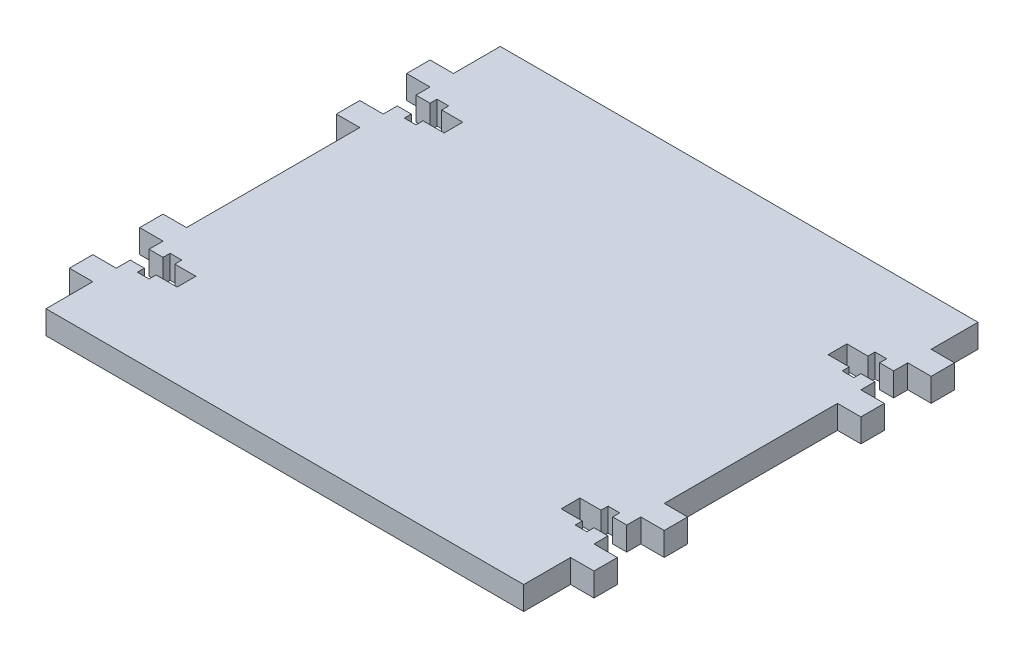
SolidWorks part; units mm, degrees
ref_plane "Front Plane" through (0, 0, 0) normal (0, 0, 1) x (1, 0, 0)
ref_plane "Top Plane" through (0, 0, 0) normal (0, 1, 0) x (1, 0, 0)
ref_plane "Right Plane" through (0, 0, 0) normal (1, 0, 0) x (0, 0, -1)
sketch "Sketch2" plane through (0, 0, 0) normal (0, 1, 0) x (1, 0, 0)
  line L16 (125.5661, 54.8651) -> (125.5661, 51.8651)
  line L17 (23.5661, 69.8651) -> (125.5661, 69.8651)
  line L42 (23.5661, 69.8651) -> (23.5661, 59.8651)
  line L43 (23.5661, -27.1349) -> (125.5661, -27.1349)
  line L44 (125.5661, 69.8651) -> (125.5661, 59.8651)
  line L49 (125.5661, 54.8651) -> (130.5661, 54.8651)
  line L50 (125.5661, 59.8651) -> (130.5661, 59.8651)
  line L51 (130.5661, 54.8651) -> (130.5661, 59.8651)
  line L52 (125.5661, 44.8651) -> (130.5661, 44.8651)
  line L53 (125.5661, 39.8651) -> (130.5661, 39.8651)
  line L54 (130.5661, 44.8651) -> (130.5661, 39.8651)
  line L55 (125.5661, 39.8651) -> (125.5661, 2.8651)
  line L56 (74.5661, 69.8651) -> (74.5661, -27.1349) construction
  line L57 (7.561, 21.3651) -> (125.5661, 21.3651) construction
  line L58 (23.5661, 39.8651) -> (18.5661, 39.8651)
  line L59 (18.5661, 44.8651) -> (18.5661, 39.8651)
  line L60 (23.5661, 44.8651) -> (18.5661, 44.8651)
  line L61 (18.5661, 54.8651) -> (18.5661, 59.8651)
  line L62 (23.5661, 54.8651) -> (18.5661, 54.8651)
  line L63 (23.5661, 59.8651) -> (18.5661, 59.8651)
  line L64 (130.5661, -12.1349) -> (130.5661, -17.1349)
  line L65 (125.5661, -17.1349) -> (130.5661, -17.1349)
  line L66 (125.5661, -12.1349) -> (130.5661, -12.1349)
  line L67 (130.5661, -2.1349) -> (130.5661, 2.8651)
  line L68 (125.5661, 2.8651) -> (130.5661, 2.8651)
  line L69 (125.5661, -2.1349) -> (130.5661, -2.1349)
  line L70 (23.5661, -17.1349) -> (18.5661, -17.1349)
  line L71 (23.5661, -12.1349) -> (18.5661, -12.1349)
  line L72 (23.5661, 2.8651) -> (18.5661, 2.8651)
  line L73 (23.5661, -2.1349) -> (18.5661, -2.1349)
  line L74 (18.5661, -12.1349) -> (18.5661, -17.1349)
  line L75 (18.5661, -2.1349) -> (18.5661, 2.8651)
  line L76 (125.5661, -2.1349) -> (125.5661, -5.1349)
  line L77 (125.5661, -17.1349) -> (125.5661, -27.1349)
  line L78 (23.5661, -17.1349) -> (23.5661, -27.1349)
  line L79 (23.5661, -2.1349) -> (23.5661, -5.1349)
  line L80 (23.5661, 39.8651) -> (23.5661, 2.8651)
  line L81 (23.5661, 54.8651) -> (23.5661, 51.8651)
  line L82 (109.561, 49.8651) -> (7.561, 49.8651) construction
  line L83 (125.5661, 51.8651) -> (122.5661, 51.8651)
  line L85 (125.5661, 47.8651) -> (122.5661, 47.8651)
  line L86 (115.5661, 51.8651) -> (115.5661, 47.8651)
  line L88 (122.5661, 51.8651) -> (122.5661, 53.3651)
  line L89 (122.5661, 53.3651) -> (120.0661, 53.3651)
  line L90 (120.0661, 51.8651) -> (120.0661, 53.3651)
  line L91 (120.0661, 51.8651) -> (115.5661, 51.8651)
  line L92 (122.5661, 47.8651) -> (122.5661, 46.3651)
  line L93 (122.5661, 46.3651) -> (120.0661, 46.3651)
  line L94 (120.0661, 47.8651) -> (120.0661, 46.3651)
  line L95 (120.0661, 47.8651) -> (115.5661, 47.8651)
  line L96 (125.5661, 47.8651) -> (125.5661, 44.8651)
  line L97 (26.5661, 51.8651) -> (26.5661, 53.3651)
  line L98 (29.0661, 51.8651) -> (29.0661, 53.3651)
  line L99 (26.5661, 53.3651) -> (29.0661, 53.3651)
  line L100 (23.5661, 51.8651) -> (26.5661, 51.8651)
  line L101 (23.5661, 47.8651) -> (26.5661, 47.8651)
  line L102 (26.5661, 47.8651) -> (26.5661, 46.3651)
  line L103 (29.0661, 47.8651) -> (29.0661, 46.3651)
  line L104 (26.5661, 46.3651) -> (29.0661, 46.3651)
  line L105 (29.0661, 47.8651) -> (33.5661, 47.8651)
  line L106 (33.5661, 51.8651) -> (33.5661, 47.8651)
  line L107 (29.0661, 51.8651) -> (33.5661, 51.8651)
  line L108 (23.5661, -9.1349) -> (26.5661, -9.1349)
  line L109 (26.5661, -9.1349) -> (26.5661, -10.6349)
  line L110 (29.0661, -9.1349) -> (29.0661, -10.6349)
  line L111 (26.5661, -10.6349) -> (29.0661, -10.6349)
  line L112 (29.0661, -9.1349) -> (33.5661, -9.1349)
  line L113 (33.5661, -9.1349) -> (33.5661, -5.1349)
  line L114 (29.0661, -5.1349) -> (33.5661, -5.1349)
  line L115 (29.0661, -5.1349) -> (29.0661, -3.6349)
  line L116 (26.5661, -5.1349) -> (26.5661, -3.6349)
  line L117 (26.5661, -3.6349) -> (29.0661, -3.6349)
  line L118 (23.5661, -5.1349) -> (26.5661, -5.1349)
  line L119 (120.0661, -9.1349) -> (120.0661, -10.6349)
  line L120 (122.5661, -10.6349) -> (120.0661, -10.6349)
  line L121 (122.5661, -9.1349) -> (122.5661, -10.6349)
  line L122 (125.5661, -9.1349) -> (122.5661, -9.1349)
  line L123 (125.5661, -5.1349) -> (122.5661, -5.1349)
  line L124 (122.5661, -5.1349) -> (122.5661, -3.6349)
  line L125 (122.5661, -3.6349) -> (120.0661, -3.6349)
  line L126 (120.0661, -5.1349) -> (120.0661, -3.6349)
  line L127 (120.0661, -5.1349) -> (115.5661, -5.1349)
  line L128 (115.5661, -9.1349) -> (115.5661, -5.1349)
  line L129 (120.0661, -9.1349) -> (115.5661, -9.1349)
  line L130 (23.5661, 47.8651) -> (23.5661, 44.8651)
  line L131 (23.5661, -9.1349) -> (23.5661, -12.1349)
  line L132 (125.5661, -9.1349) -> (125.5661, -12.1349)
  dimension "D1" = 102
  dimension "D2" = 97
  dimension "D3" = 3
  dimension "D4" = 3
  dimension "D5" = 10
  dimension "D6" = 5
  dimension "D7" = 10
  dimension "D8" = 10
  dimension "D9" = 2.5
  dimension "D10" = 1.5
  dimension "D11" = 48.5
extrude "Boss-Extrude1" add sketch "Sketch2" along normal blind 5
